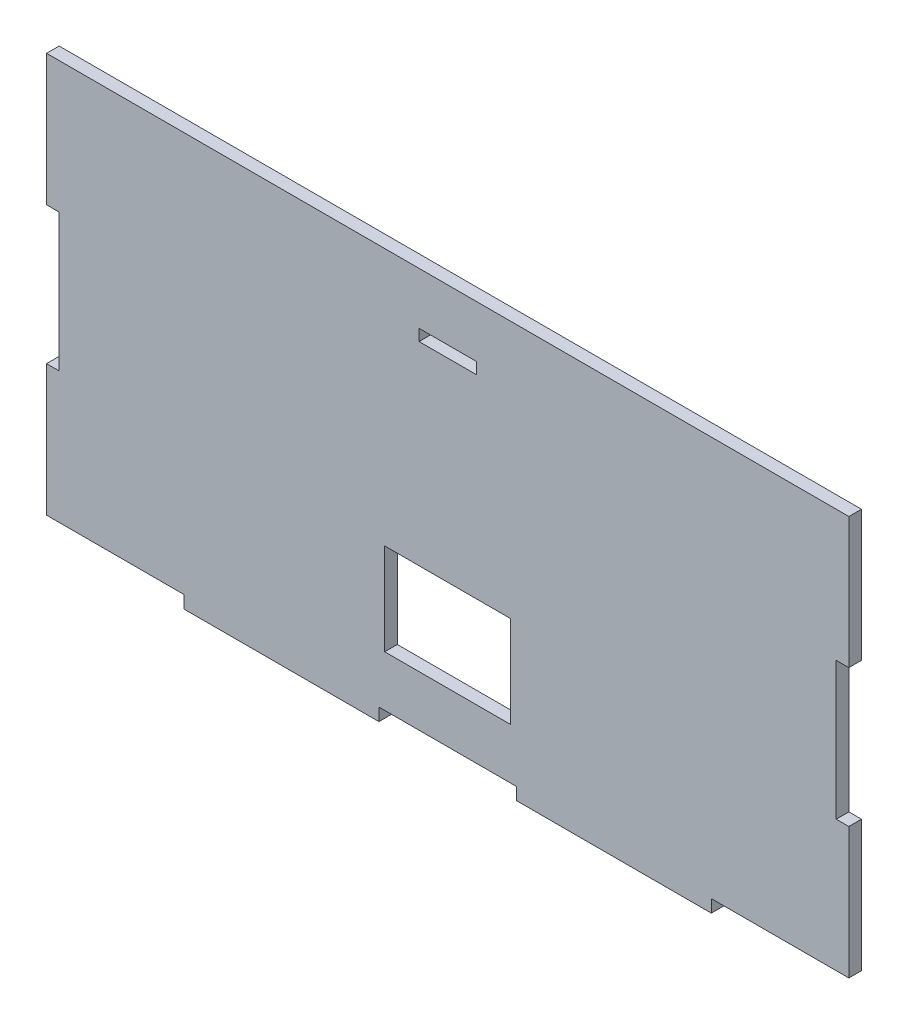
SolidWorks part; units mm, degrees
ref_plane "Alzado" through (0, 0, 0) normal (0, 0, 1) x (1, 0, 0)
ref_plane "Planta" through (0, 0, 0) normal (0, 1, 0) x (1, 0, 0)
ref_plane "Vista lateral" through (0, 0, 0) normal (1, 0, 0) x (0, 0, -1)
sketch "Croquis2" plane through (0, 0, 0) normal (0, 0, 1) x (1, 0, 0)
  line L0 (-33.6295, 28.3804) -> (316.3705, 28.3804)
  line L1 (-33.6295, 28.3804) -> (-33.6295, -28.8696)
  line L2 (316.3705, 28.3804) -> (316.3705, -28.7261)
  line L3 (316.3705, -88.7261) -> (310.8705, -88.7261)
  line L4 (-33.6295, -88.8696) -> (-28.1295, -88.8696)
  line L5 (-28.1295, -88.8696) -> (-28.1295, -28.8696)
  line L6 (-28.1295, -28.8696) -> (-33.6295, -28.8696)
  line L7 (310.8705, -88.7261) -> (310.8705, -28.7261)
  line L8 (310.8705, -28.7261) -> (316.3705, -28.7261)
  line L9 (-33.6295, -88.8696) -> (-33.6295, -146.1196)
  line L10 (316.3705, -88.7261) -> (316.3705, -145.9761)
  line L11 (-33.6295, -146.1196) -> (26.3705, -146.1196)
  line L12 (26.3705, -146.1196) -> (26.3705, -151.6196)
  line L13 (316.3705, -145.9761) -> (256.3705, -145.9761)
  line L14 (256.3705, -145.9761) -> (256.3705, -151.4761)
  line L15 (111.3705, -146.1196) -> (171.3705, -146.1196)
  line L16 (111.3705, -146.1196) -> (111.3705, -151.6196)
  line L17 (111.3705, -151.6196) -> (26.3705, -151.6196)
  line L18 (171.3705, -146.1196) -> (171.3705, -151.4761)
  line L19 (171.3705, -151.4761) -> (256.3705, -151.4761)
  line L20 (-33.6295, -178.8117) -> (316.3705, -178.8117) construction
  line L21 (141.3705, -178.8117) -> (141.3705, -109.1525) construction
  line L22 (113.8705, -123.978) -> (113.8705, -83.978)
  line L23 (113.8705, -83.978) -> (168.8705, -83.978)
  line L24 (168.8705, -83.978) -> (168.8705, -123.978)
  line L25 (168.8705, -123.978) -> (113.8705, -123.978)
  line L26 (168.8705, -103.978) -> (183.8705, -103.978) construction
  line L27 (153.8705, 0.7237) -> (153.8705, 5.7237)
  line L28 (153.8705, 0.7237) -> (128.8705, 0.7237)
  line L29 (128.8705, 0.7237) -> (128.8705, 5.7237)
  line L30 (153.8705, 5.7237) -> (128.8705, 5.7237)
  line L31 (141.3705, -74.2763) -> (141.3705, 5.7237) construction
  line L32 (106.3705, -34.2763) -> (176.3705, -34.2763) construction
  dimension "D1" = 350
  dimension "D2" = 174.5
extrude "Saliente-Extruir3" add sketch "Croquis2" along normal blind 5.5
